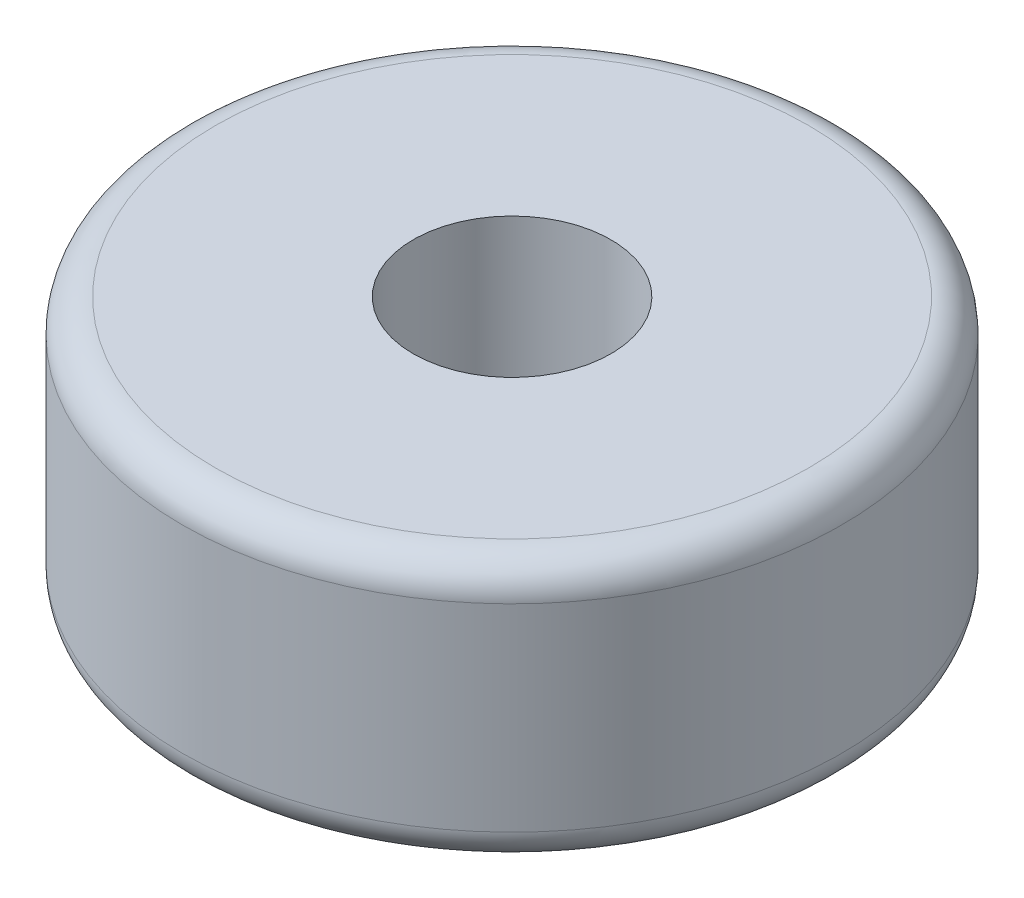
SolidWorks part; units mm, degrees
ref_plane "Front Plane" through (0, 0, 0) normal (0, 0, 1) x (1, 0, 0)
ref_plane "Top Plane" through (0, 0, 0) normal (0, 1, 0) x (1, 0, 0)
ref_plane "Right Plane" through (0, 0, 0) normal (1, 0, 0) x (0, 0, -1)
sketch "Sketch1" plane through (0, 0, 0) normal (0, 1, 0) x (1, 0, 0)
  circle A0 centre (0, 0) radius 10
  circle A1 centre (0, 0) radius 3
  dimension "D1" = 6
  dimension "D2" = 20
extrude "Boss-Extrude1" add sketch "Sketch1" along normal blind 8
fillet "Fillet1" radius 1 2 edges at (0, 0, 10) (0, 8, 10)
